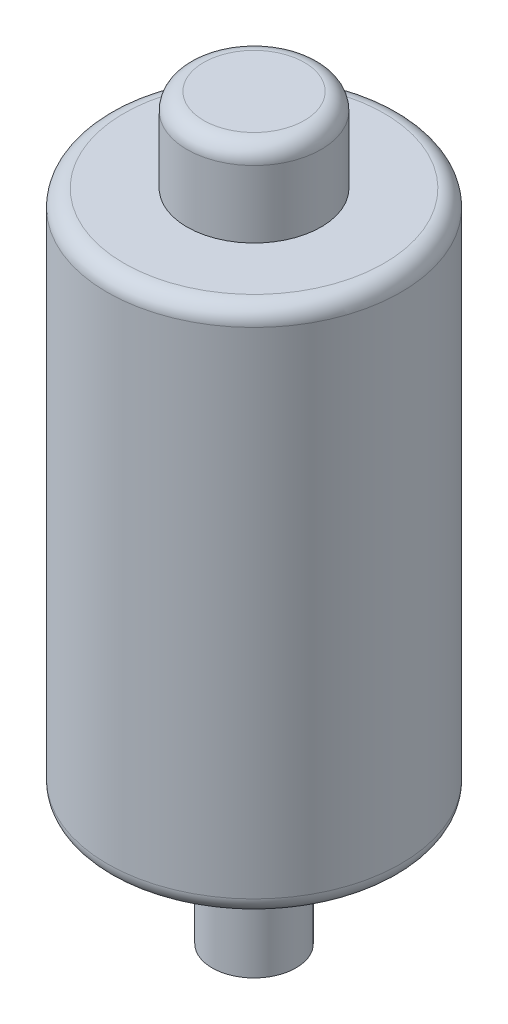
SolidWorks part; units mm, degrees
ref_plane "Front Plane" through (0, 0, 0) normal (0, 0, 1) x (1, 0, 0)
ref_plane "Top Plane" through (0, 0, 0) normal (0, 1, 0) x (1, 0, 0)
ref_plane "Right Plane" through (0, 0, 0) normal (1, 0, 0) x (0, 0, -1)
sketch "Sketch1" plane through (0, 0, 0) normal (0, 1, 0) x (1, 0, 0)
  circle A0 centre (0, 0) radius 6.35
  dimension "D1" = 12.7
extrude "Boss-Extrude1" add sketch "Sketch1" along normal blind 19.05
sketch "Sketch3" plane through (0, 19.05, 0) normal (0, 1, 0) x (1, 0, 0)
  circle A0 centre (0, 0) radius 22.225
extrude "Boss-Extrude2" add sketch "Sketch3" along normal blind 80.01
sketch "Sketch4" plane through (0, 99.06, 0) normal (0, 1, 0) x (1, 0, 0)
  circle A0 centre (0, 0) radius 10.16
extrude "Boss-Extrude3" add sketch "Sketch4" along normal blind 12.7
fillet "Fillet2" radius 2.54 1 edges at (0, 111.76, 10.16)
fillet "Fillet3" radius 2.54 1 edges at (0, 99.06, 22.225)
fillet "Fillet4" radius 2.54 1 edges at (0, 19.05, 22.225)
ref_plane "Plane1" through (0, 0, -10.16) normal (0, 0, -1) x (-1, 0, 0)
sketch "Sketch5" plane through (0, 0, -10.16) normal (0, 0, -1) x (-1, 0, 0)
  circle A0 centre (0, 104.5313) radius 0.9486
extrude "Cut-Extrude1" cut sketch "Sketch5" against normal blind 2.54
